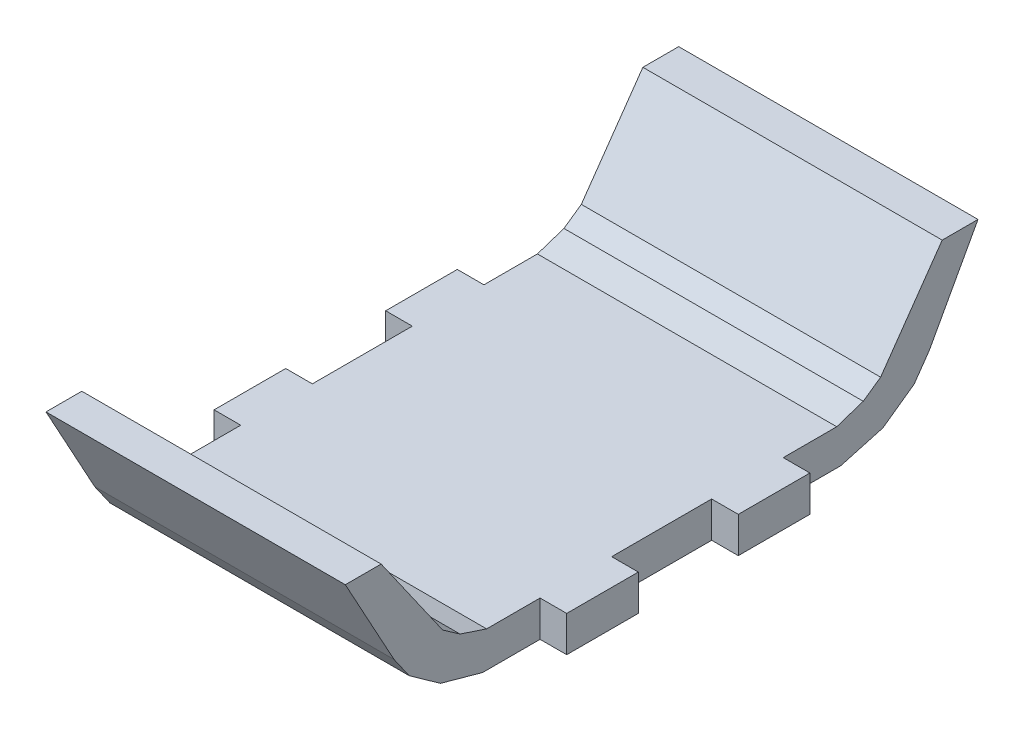
SolidWorks part; units mm, degrees
ref_plane "정면" through (0, 0, 0) normal (0, 0, 1) x (1, 0, 0)
ref_plane "윗면" through (0, 0, 0) normal (0, 1, 0) x (1, 0, 0)
ref_plane "우측면" through (0, 0, 0) normal (1, 0, 0) x (0, 0, -1)
sketch "스케치2" plane through (0, 0, 0) normal (0, 1, 0) x (1, 0, 0)
  line L0 (0, -55) -> (0, 55) construction
  line L1 (-10.45, 12.5) -> (10.45, 12.5)
  line L2 (-10.45, 12.5) -> (-10.45, 8.49)
  line L3 (-10.45, -12.5) -> (10.45, -12.5)
  line L4 (10.45, 12.5) -> (10.45, 8.49)
  line L7 (-10.45, 8.49) -> (-12.3099, 8.49)
  line L9 (-10.45, 3.49) -> (-12.3099, 3.49)
  line L10 (-12.3099, 8.49) -> (-12.3099, 3.49)
  line L11 (-10.45, -3.49) -> (-12.3099, -3.49)
  line L13 (-10.45, -8.49) -> (-12.3099, -8.49)
  line L14 (-12.3099, -3.49) -> (-12.3099, -8.49)
  line L15 (10.45, 3.49) -> (12.3099, 3.49)
  line L16 (12.3099, 8.49) -> (12.3099, 3.49)
  line L17 (10.45, 8.49) -> (12.3099, 8.49)
  line L19 (10.45, -8.49) -> (12.3099, -8.49)
  line L20 (12.3099, -3.49) -> (12.3099, -8.49)
  line L21 (10.45, -3.49) -> (12.3099, -3.49)
  line L23 (10.45, 3.49) -> (10.45, -3.49)
  line L24 (10.45, -8.49) -> (10.45, -12.5)
  line L25 (-10.45, -8.49) -> (-10.45, -12.5)
  line L26 (-10.45, 3.49) -> (-10.45, -3.49)
  point P0 (0, 0)
  dimension "D1" = 20.9
  dimension "D2" = 25
  dimension "D3" = 5
  dimension "D4" = 5
  dimension "D5" = 6.98
  dimension "D6" = 4.01
extrude "보스-돌출1" add sketch "스케치2" along normal blind 2.5
sketch "스케치3" plane through (0, 0, 0) normal (1, 0, 0) x (0, 0, -1)
  line L0 (0, 0) -> (12.5, 0)
  line L4 (12.223, 2.5) -> (-12.3479, 2.5)
  line L8 (12.5, 0) -> (15.4465, 0.8163)
  line L9 (-12.5, 0) -> (0, 0)
  line L10 (-18.686, 3.8818) -> (-22.0881, 10.1037)
  line L11 (17.6288, 2.372) -> (15.4465, 0.8163)
  line L13 (-17.6288, 2.372) -> (-15.4465, 0.8163)
  line L14 (-14.0765, 3.1152) -> (-15.2894, 3.9645)
  line L15 (12.223, 2.5) -> (14.0765, 3.1152)
  line L17 (-15.2894, 3.9645) -> (-19.5881, 10.1037)
  line L20 (-12.5, 0) -> (-15.4465, 0.8163)
  line L22 (-18.686, 3.8818) -> (-17.6288, 2.372)
  line L23 (0, 1.375) -> (0, -1.375) construction
  line L24 (-22.0881, 10.1037) -> (-19.5881, 10.1037)
  line L25 (14.0765, 3.1152) -> (15.2894, 3.9645)
  line L26 (13.5582, 3.0585) -> (13.5, 3.0053)
  line L29 (18.686, 3.8818) -> (17.6288, 2.372)
  line L30 (14.0765, 3.1152) -> (15.2894, 3.9645)
  line L31 (18.686, 3.8818) -> (22.0881, 10.1037)
  line L32 (15.2894, 3.9645) -> (19.5881, 10.1037)
  line L33 (-12.5, 0) -> (-12.5, 2.5)
  line L34 (22.0881, 10.1037) -> (19.5881, 10.1037)
  line L35 (12.5, 0) -> (12.5, 2.5)
  line L36 (-12.223, 2.5) -> (-14.0765, 3.1152)
  line L37 (-12.223, 2.5) -> (-12.3479, 2.5)
  line L38 (-12.5, 2.5) -> (-8.49, 2.5) construction
  dimension "D1" = 2.5
  dimension "D4" = 55
  dimension "D5" = 200
  dimension "D7" = 1.4807
  dimension "D8" = 2.6801
ref_plane "평면1" through (0, 5, 0) normal (0, 1, 0) x (1, 0, 0)
extrude "보스-돌출2" add sketch "스케치3" along normal blind 10.45 and the other way blind 10.45
